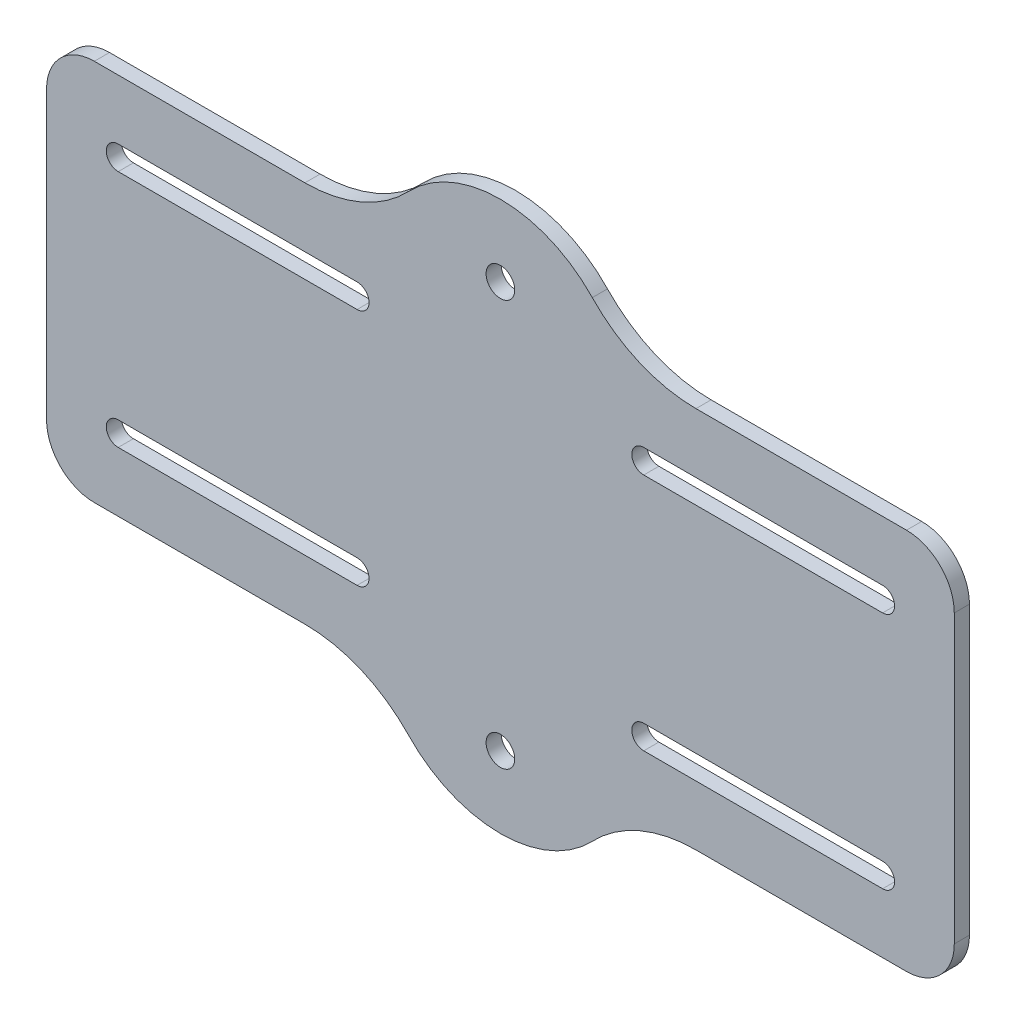
SolidWorks part; units mm, degrees
ref_plane "Front Plane" through (0, 0, 0) normal (0, 0, 1) x (1, 0, 0)
ref_plane "Top Plane" through (0, 0, 0) normal (0, 1, 0) x (1, 0, 0)
ref_plane "Right Plane" through (0, 0, 0) normal (1, 0, 0) x (0, 0, -1)
sketch "Sketch1" plane through (0, 0, 0) normal (0, 0, 1) x (1, 0, 0)
  line L0 (30, 25) -> (80, 25) construction
  line L1 (-95, -40) -> (-25, -40)
  line L2 (-95, -40) -> (-95, 40)
  line L3 (-95, 40) -> (-25, 40)
  line L4 (95, -40) -> (95, 40)
  line L9 (-95, 0) -> (95, 0) construction
  line L10 (0, 57.5) -> (0, -57.5) construction
  line L11 (30, 27.5) -> (80, 27.5)
  line L14 (30, 22.5) -> (80, 22.5)
  line L17 (30, -25) -> (80, -25) construction
  line L20 (-95, 0) -> (95, 0) construction
  line L21 (30, -27.5) -> (80, -27.5)
  line L22 (30, -22.5) -> (80, -22.5)
  line L23 (-30, 25) -> (-80, 25) construction
  line L24 (-30, 27.5) -> (-80, 27.5)
  line L25 (-30, 22.5) -> (-80, 22.5)
  line L26 (-30, -25) -> (-80, -25) construction
  line L27 (-30, -27.5) -> (-80, -27.5)
  line L28 (-30, -22.5) -> (-80, -22.5)
  line L29 (10, 55.5493) -> (10, -55.5493) construction
  line L30 (-10, 55.5493) -> (-10, -55.5493) construction
  line L37 (25, 40) -> (95, 40)
  line L38 (25, -40) -> (95, -40)
  circle A8 centre (0, 42.5) radius 3
  circle A9 centre (0, -42.5) radius 3
  arc A23 (30, 27.5) -> (30, 22.5) centre (30, 25) ccw
  arc A24 (80, 22.5) -> (80, 27.5) centre (80, 25) ccw
  arc A25 (30, -27.5) -> (30, -22.5) centre (30, -25) cw
  arc A26 (80, -22.5) -> (80, -27.5) centre (80, -25) cw
  arc A27 (-30, 27.5) -> (-30, 22.5) centre (-30, 25) cw
  arc A28 (-80, 22.5) -> (-80, 27.5) centre (-80, 25) cw
  arc A29 (-30, -27.5) -> (-30, -22.5) centre (-30, -25) ccw
  arc A30 (-80, -22.5) -> (-80, -27.5) centre (-80, -25) ccw
  arc A31 (-25, 40) -> (25, 40) centre (0, 30.8929) cw
  arc A32 (-25, -40) -> (25, -40) centre (0, -30.8929) ccw
  point P0 (0, 0)
  point P8 (55, 25)
  point P14 (0, 0)
  point P21 (55, -25)
  point P28 (-55, 25)
  point P35 (-55, -25)
  dimension "D8" = 6
  dimension "D4" = 50
  dimension "D5" = 15
  dimension "D6" = 20
  dimension "D9" = 20
  dimension "D1" = 80
  dimension "D2" = 50
  dimension "D3" = 5
  dimension "D7" = 85
  dimension "D10" = 50
  dimension "D11" = 15
extrude "Boss-Extrude1" add sketch "Sketch1" along normal blind 3.175
fillet "Fillet1" radius 10 4 edges at (-95, -40, 1.5875) (-95, 40, 1.5875) (95, -40, 1.5875) (95, 40, 1.5875)
fillet "Fillet2" radius 30 4 edges at (25, -40, 1.5875) (-25, -40, 1.5875) (25, 40, 1.5875) (-25, 40, 1.5875)
